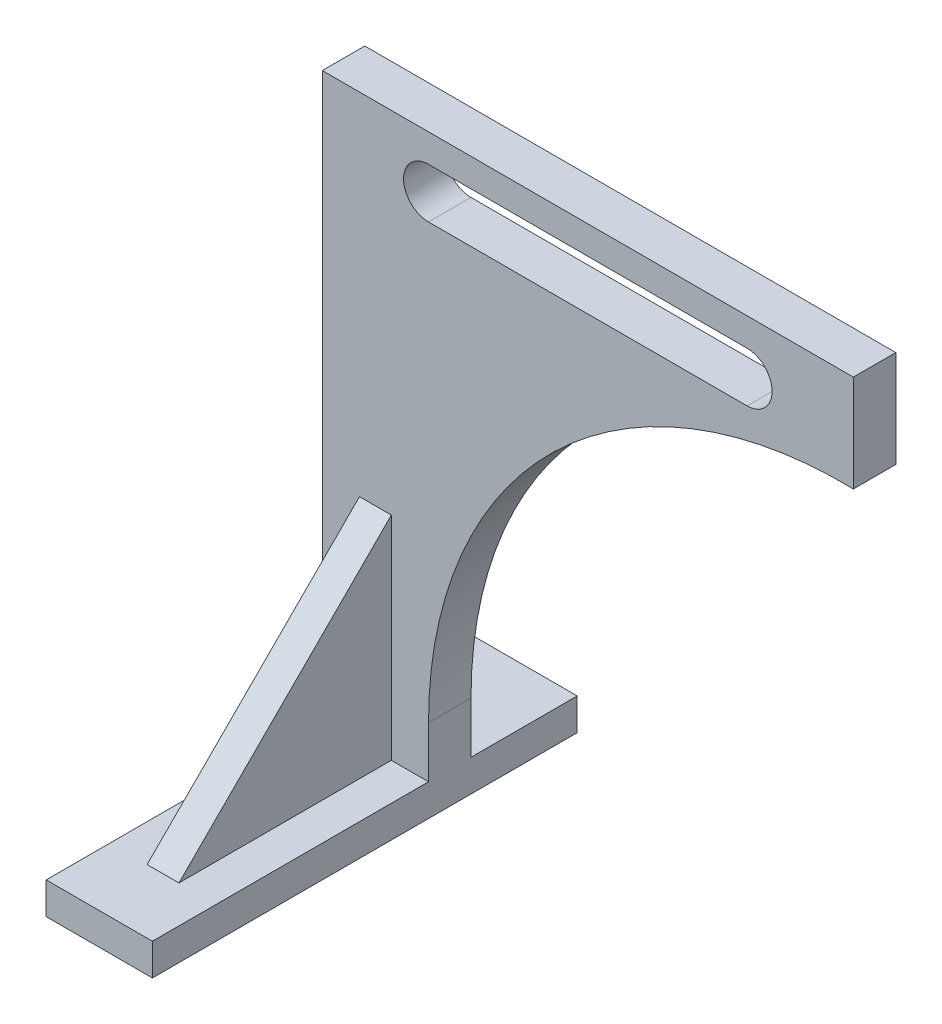
SolidWorks part; units mm, degrees
ref_plane "Front Plane" through (0, 0, 0) normal (0, 0, 1) x (1, 0, 0)
ref_plane "Top Plane" through (0, 0, 0) normal (0, 1, 0) x (1, 0, 0)
ref_plane "Right Plane" through (0, 0, 0) normal (1, 0, 0) x (0, 0, -1)
sketch "Sketch1" plane through (0, 0, 0) normal (0, 0, 1) x (1, 0, 0)
  line L1 (-75, -132.5) -> (-125, -132.5)
  line L2 (125, 86.8752) -> (125, 132.5)
  line L3 (125, 132.5) -> (-125, 132.5)
  line L4 (-125, -132.5) -> (-125, 132.5)
  line L5 (-75, -132.5) -> (-75, -108.3682)
  line L7 (-75, -132.5) -> (-75, 132.5) construction
  arc A1 (125, 86.8752) -> (-75, -108.3682) centre (120.3, -108.3682) ccw
  point P0 (0, 0)
  point P7 (-70.3, 132.5)
  point P8 (-70.3, -132.5)
  point P9 (-70.3, 132.5)
  dimension "D2" = 50
  dimension "D4" = 195.3
  dimension "D1" = 250
  dimension "D3" = 132.5
  dimension "D5" = 132.5
extrude "Boss-Extrude1" add sketch "Sketch1" against normal blind 20
sketch "Sketch2" plane through (0, 0, 0) normal (0, 0, 1) x (1, 0, 0)
  line L0 (-125, 132.5) -> (-125, -132.5) construction
  line L2 (-125, -132.5) -> (-75, -132.5) construction
  line L8 (-75, 107.5) -> (75, 107.5) construction
  line L9 (-75, 119.25) -> (75, 119.25)
  line L10 (-75, 95.75) -> (75, 95.75)
  arc A1 (-75, 119.25) -> (-75, 95.75) centre (-75, 107.5) ccw
  arc A2 (75, 95.75) -> (75, 119.25) centre (75, 107.5) ccw
  point P17 (0, 107.5)
  dimension "D4" = 11.75
  dimension "D1" = 50
  dimension "D2" = 50
  dimension "D3" = 200
  dimension "D5" = 240
  dimension "D6" = 265
extrude "Cut-Extrude1" cut sketch "Sketch2" against normal blind 80
sketch "Sketch3" plane through (0, 0, 0) normal (0, 0, 1) x (1, 0, 0)
  line L0 (-125, -132.5) -> (-75, -132.5) construction
  line L1 (-107.5, -132.5) -> (-92.5, -132.5)
  line L2 (-107.5, -132.5) -> (-107.5, -32.5)
  line L3 (-107.5, -32.5) -> (-92.5, -32.5)
  line L4 (-92.5, -132.5) -> (-92.5, -32.5)
  line L5 (-75, 95.75) -> (75, 95.75) construction
  line L7 (-125, 132.5) -> (-125, -132.5) construction
  dimension "D1" = 0
  dimension "D2" = 100
  dimension "D3" = 17.5
  dimension "D4" = 15
  dimension "D5" = 200
  dimension "D6" = 36.75
extrude "Boss-Extrude2" add sketch "Sketch3" along normal blind 100
sketch "Sketch10" plane through (0, -132.5, 0) normal (0, -1, 0) x (1, 0, 0)
  line L0 (-107.5, 100) -> (-92.5, 100) construction
  line L1 (-75, -70) -> (-125, -70)
  line L2 (-75, -70) -> (-75, 130)
  line L3 (-75, 130) -> (-125, 130)
  line L4 (-125, -70) -> (-125, 130)
  line L5 (-107.5, 100) -> (-107.5, 0) construction
  line L6 (-92.5, 100) -> (-92.5, 0) construction
  line L7 (-75, -20) -> (125, -20) construction
  dimension "D1" = 30
  dimension "D2" = 17.5
  dimension "D3" = 17.5
  dimension "D4" = 50
extrude "Boss-Extrude4" add sketch "Sketch10" along normal blind 15
sketch "Sketch11" plane through (-92.5, 0, 0) normal (1, 0, 0) x (0, 0, -1)
  line L0 (0, -32.5) -> (-100, -132.5)
  line L1 (-100, -132.5) -> (-100, -32.5)
  line L2 (-100, -32.5) -> (0, -32.5)
extrude "Cut-Extrude3" cut sketch "Sketch11" against normal blind 166
